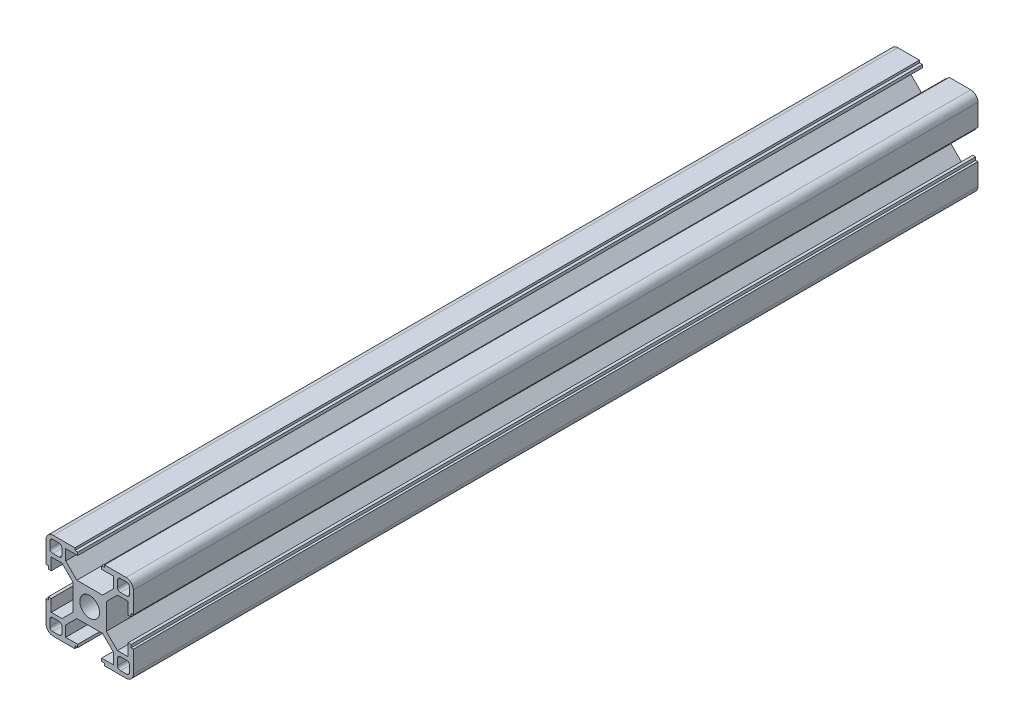
SolidWorks part; units mm, degrees
material "6061-T6 (SS)"
ref_plane "前视基准面" through (0, 0, 0) normal (0, 0, 1) x (1, 0, 0)
ref_plane "上视基准面" through (0, 0, 0) normal (0, 1, 0) x (1, 0, 0)
ref_plane "右视基准面" through (0, 0, 0) normal (1, 0, 0) x (0, 0, -1)
sketch "Sketch1" plane through (0, 0, 0) normal (0, 0, 1) x (1, 0, 0)
  line L0 (-5.1, 15) -> (-5.1, 14.2)
  line L1 (-12.5, -15) -> (12.5, -15)
  line L2 (-15, -12.5) -> (-15, 12.5)
  line L3 (-12.5, 15) -> (12.5, 15)
  line L4 (15, -12.5) -> (15, 12.5)
  line L5 (-15, -15) -> (15, 15) construction
  line L6 (-15, 15) -> (15, -15) construction
  line L7 (-5.1, 14.2) -> (-4.1, 14.2)
  line L8 (-4.1, 14.2) -> (-4.1, 13.2)
  line L9 (-4.1, 13.2) -> (-8.25, 13.2)
  line L10 (-8.25, 13.2) -> (-8.25, 9.5228)
  line L11 (-8.25, 9.5228) -> (-4.4272, 5.7)
  line L12 (-4.4272, 5.7) -> (4.4272, 5.7)
  line L13 (-5.1, 15) -> (5.1, 15)
  line L14 (0, 15) -> (0, 5.7) construction
  line L15 (8.25, 9.5228) -> (4.4272, 5.7)
  line L16 (8.25, 13.2) -> (8.25, 9.5228)
  line L17 (4.1, 13.2) -> (8.25, 13.2)
  line L18 (4.1, 14.2) -> (4.1, 13.2)
  line L19 (5.1, 14.2) -> (4.1, 14.2)
  line L20 (5.1, 15) -> (5.1, 14.2)
  line L21 (15, 5.1) -> (14.2, 5.1)
  line L22 (14.2, 5.1) -> (14.2, 4.1)
  line L23 (14.2, 4.1) -> (13.2, 4.1)
  line L24 (13.2, 4.1) -> (13.2, 8.25)
  line L25 (13.2, 8.25) -> (9.5228, 8.25)
  line L26 (9.5228, 8.25) -> (5.7, 4.4272)
  line L27 (5.7, 4.4272) -> (5.7, -4.4272)
  line L28 (15, 5.1) -> (15, -5.1)
  line L29 (9.5228, -8.25) -> (5.7, -4.4272)
  line L30 (13.2, -8.25) -> (9.5228, -8.25)
  line L31 (13.2, -4.1) -> (13.2, -8.25)
  line L32 (14.2, -4.1) -> (13.2, -4.1)
  line L33 (14.2, -5.1) -> (14.2, -4.1)
  line L34 (15, -5.1) -> (14.2, -5.1)
  line L35 (15, 0) -> (5.7, 0) construction
  line L36 (5.1, -15) -> (5.1, -14.2)
  line L37 (5.1, -14.2) -> (4.1, -14.2)
  line L38 (4.1, -14.2) -> (4.1, -13.2)
  line L39 (4.1, -13.2) -> (8.25, -13.2)
  line L40 (8.25, -13.2) -> (8.25, -9.5228)
  line L41 (8.25, -9.5228) -> (4.4272, -5.7)
  line L42 (4.4272, -5.7) -> (-4.4272, -5.7)
  line L43 (5.1, -15) -> (-5.1, -15)
  line L44 (-8.25, -9.5228) -> (-4.4272, -5.7)
  line L45 (-8.25, -13.2) -> (-8.25, -9.5228)
  line L46 (-4.1, -13.2) -> (-8.25, -13.2)
  line L47 (-4.1, -14.2) -> (-4.1, -13.2)
  line L48 (-5.1, -14.2) -> (-4.1, -14.2)
  line L49 (-5.1, -15) -> (-5.1, -14.2)
  line L50 (0, -15) -> (0, -5.7) construction
  line L51 (-15, -5.1) -> (-14.2, -5.1)
  line L52 (-14.2, -5.1) -> (-14.2, -4.1)
  line L53 (-14.2, -4.1) -> (-13.2, -4.1)
  line L54 (-13.2, -4.1) -> (-13.2, -8.25)
  line L55 (-13.2, -8.25) -> (-9.5228, -8.25)
  line L56 (-9.5228, -8.25) -> (-5.7, -4.4272)
  line L57 (-5.7, -4.4272) -> (-5.7, 4.4272)
  line L58 (-15, -5.1) -> (-15, 5.1)
  line L59 (-9.5228, 8.25) -> (-5.7, 4.4272)
  line L60 (-13.2, 8.25) -> (-9.5228, 8.25)
  line L61 (-13.2, 4.1) -> (-13.2, 8.25)
  line L62 (-14.2, 4.1) -> (-13.2, 4.1)
  line L63 (-14.2, 5.1) -> (-14.2, 4.1)
  line L64 (-15, 5.1) -> (-14.2, 5.1)
  line L65 (-15, 0) -> (-5.7, 0) construction
  line L66 (0, 0) -> (0, 5.7) construction
  circle A0 centre (0, 0) radius 3.4
  arc A1 (-12.5, -15) -> (-15, -12.5) centre (-12.5, -12.5) cw
  arc A2 (12.5, -15) -> (15, -12.5) centre (12.5, -12.5) ccw
  arc A3 (12.5, 15) -> (15, 12.5) centre (12.5, 12.5) cw
  arc A4 (-15, 12.5) -> (-12.5, 15) centre (-12.5, 12.5) cw
  point P0 (0, 0)
  dimension "D3" = 6.8
  dimension "D12" = 2.5
  dimension "D1" = 30
  dimension "D2" = 30
  dimension "D4" = 16.5
  dimension "D5" = 8.2
  dimension "D6" = 10.2
  dimension "D7" = 7.5
  dimension "D9" = 1.8
  dimension "D10" = 1.8
  dimension "D11" = 0.8
  dimension "D8" = 4
extrude "Extrude1" add sketch "Sketch1" along normal blind 290 contours A4 L2 L64 L63 L62 L61 L60 L59 L57 L56 L55 L54 L53 L52 L51 A1 L1 L49 L48 L47 L46 L45 L44 L42 L41 L40 L39 L38 L37 L36 A2 L4 L34 L33 L32 L31 L30 L29 L27 L26 L25 L24 L23 L22 L21 A3 L3 L20
sketch "Sketch2" plane through (0, 0, 290) normal (0, 0, 1) x (1, 0, 0)
  line L0 (13.7, 12.7) -> (13.7, 10.55)
  line L1 (-12.7, 13.7) -> (-10.55, 13.7)
  line L2 (-13.7, 12.7) -> (-13.7, 10.55)
  line L3 (-12.7, 9.55) -> (-10.55, 9.55)
  line L4 (-9.55, 12.7) -> (-9.55, 10.55)
  line L5 (-13.7, 13.7) -> (-9.55, 9.55) construction
  line L6 (-13.7, 9.55) -> (-9.55, 13.7) construction
  line L7 (12.7, 13.7) -> (10.55, 13.7)
  line L8 (9.55, 12.7) -> (9.55, 10.55)
  line L9 (12.7, 9.55) -> (10.55, 9.55)
  line L10 (12.7, -13.7) -> (10.55, -13.7)
  line L11 (13.7, -12.7) -> (13.7, -10.55)
  line L12 (12.7, -9.55) -> (10.55, -9.55)
  line L13 (9.55, -12.7) -> (9.55, -10.55)
  line L14 (-13.7, -12.7) -> (-13.7, -10.55)
  line L15 (-12.7, -13.7) -> (-10.55, -13.7)
  line L16 (-9.55, -12.7) -> (-9.55, -10.55)
  line L17 (-12.7, -9.55) -> (-10.55, -9.55)
  line L18 (0, 0) -> (-9.55, 9.55) construction
  line L19 (-12.5, 15) -> (-5.1, 15) construction
  line L20 (-15, 5.1) -> (-15, 12.5) construction
  line L21 (-13.2, 8.25) -> (-9.5228, 8.25) construction
  line L22 (-8.25, 13.2) -> (-8.25, 9.5228) construction
  arc A0 (-13.7, -12.7) -> (-12.7, -13.7) centre (-12.7, -12.7) ccw
  arc A1 (-10.55, -13.7) -> (-9.55, -12.7) centre (-10.55, -12.7) ccw
  arc A2 (-9.55, -10.55) -> (-10.55, -9.55) centre (-10.55, -10.55) ccw
  arc A3 (-13.7, -10.55) -> (-12.7, -9.55) centre (-12.7, -10.55) cw
  arc A4 (13.7, -10.55) -> (12.7, -9.55) centre (12.7, -10.55) ccw
  arc A5 (12.7, -13.7) -> (13.7, -12.7) centre (12.7, -12.7) ccw
  arc A6 (10.55, -13.7) -> (9.55, -12.7) centre (10.55, -12.7) cw
  arc A7 (10.55, -9.55) -> (9.55, -10.55) centre (10.55, -10.55) ccw
  arc A8 (13.7, 12.7) -> (12.7, 13.7) centre (12.7, 12.7) ccw
  arc A9 (13.7, 10.55) -> (12.7, 9.55) centre (12.7, 10.55) cw
  arc A10 (9.55, 10.55) -> (10.55, 9.55) centre (10.55, 10.55) ccw
  arc A11 (10.55, 13.7) -> (9.55, 12.7) centre (10.55, 12.7) ccw
  arc A12 (-10.55, 13.7) -> (-9.55, 12.7) centre (-10.55, 12.7) cw
  arc A13 (-10.55, 9.55) -> (-9.55, 10.55) centre (-10.55, 10.55) ccw
  arc A14 (-13.7, 10.55) -> (-12.7, 9.55) centre (-12.7, 10.55) ccw
  arc A15 (-12.7, 13.7) -> (-13.7, 12.7) centre (-12.7, 12.7) ccw
  point P0 (-11.625, 11.625)
  dimension "D2" = 1
  dimension "D3" = 1.3
  dimension "D4" = 1.3
  dimension "D5" = 1.3
  dimension "D6" = 1.3
  dimension "D1" = 4
extrude "Extrude2" cut sketch "Sketch2" against normal through all
